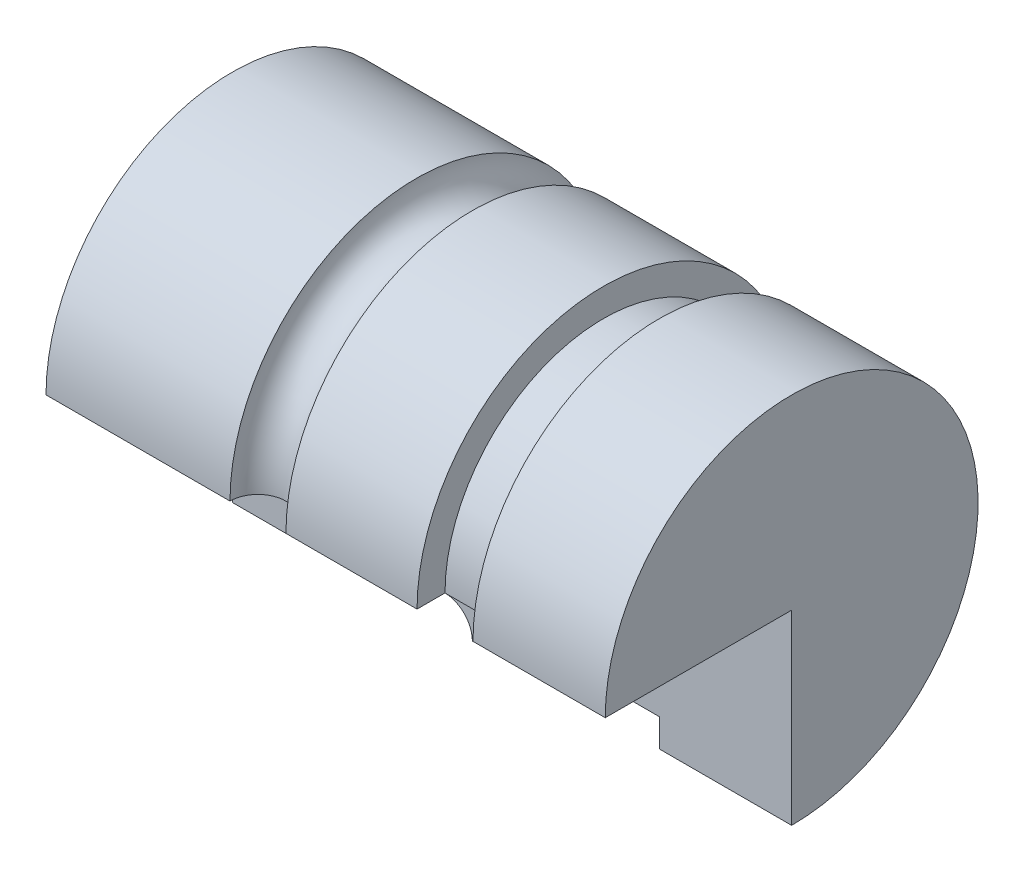
SolidWorks part; units mm, degrees
ref_plane "Plan de face" through (0, 0, 0) normal (0, 0, 1) x (1, 0, 0)
ref_plane "Plan de dessus" through (0, 0, 0) normal (0, 1, 0) x (1, 0, 0)
ref_plane "Plan de droite" through (0, 0, 0) normal (1, 0, 0) x (0, 0, -1)
sketch "Esquisse1" plane through (0, 0, 0) normal (0, 0, 1) x (1, 0, 0)
  line L0 (0, 0) -> (51.7301, 0) construction
  line L1 (0, 0) -> (0, 10)
  line L2 (0, 10) -> (30, 10)
  line L3 (30, 10) -> (30, 0)
  line L4 (0, 0) -> (30, 0)
  dimension "D1" = 30
  dimension "D2" = 10
revolve "Révolution2" add sketch "Esquisse1" angle 360 about L0
sketch "Esquisse4" plane through (0, 0, 0) normal (0, 1, 0) x (1, 0, 0)
  line L0 (30, 10) -> (0, 10) construction
  line L1 (30, 10) -> (0, 10) construction
  line L2 (19.9045, 11.0013) -> (22.9045, 11.0013)
  line L3 (19.9045, 11.0013) -> (19.9045, 8.5)
  line L4 (19.9045, 8.5) -> (22.9045, 8.5)
  line L5 (22.9045, 11.0013) -> (22.9045, 8.5)
  line L6 (0, 0) -> (31.5281, 0) construction
  circle A0 centre (11.3707, 10) radius 1.5
  dimension "D1" = 3
  dimension "D2" = 3
  dimension "D3" = 1.5
revolve "Enlèvement de matière-Révolution1" cut sketch "Esquisse4" angle 360 about L6
sketch "Esquisse5" plane through (30, 0, 0) normal (1, 0, 0) x (0, 0, -1)
  line L1 (0, 0) -> (-24.7381, 0)
  line L2 (0, 0) -> (0, -14.7217)
  line L3 (0, -14.7217) -> (-24.7381, -14.7217)
  line L4 (-24.7381, 0) -> (-24.7381, -14.7217)
extrude "Enlèv. mat.-Extru.2" cut sketch "Esquisse5" against normal through all contours L4 L3 L2 L1
